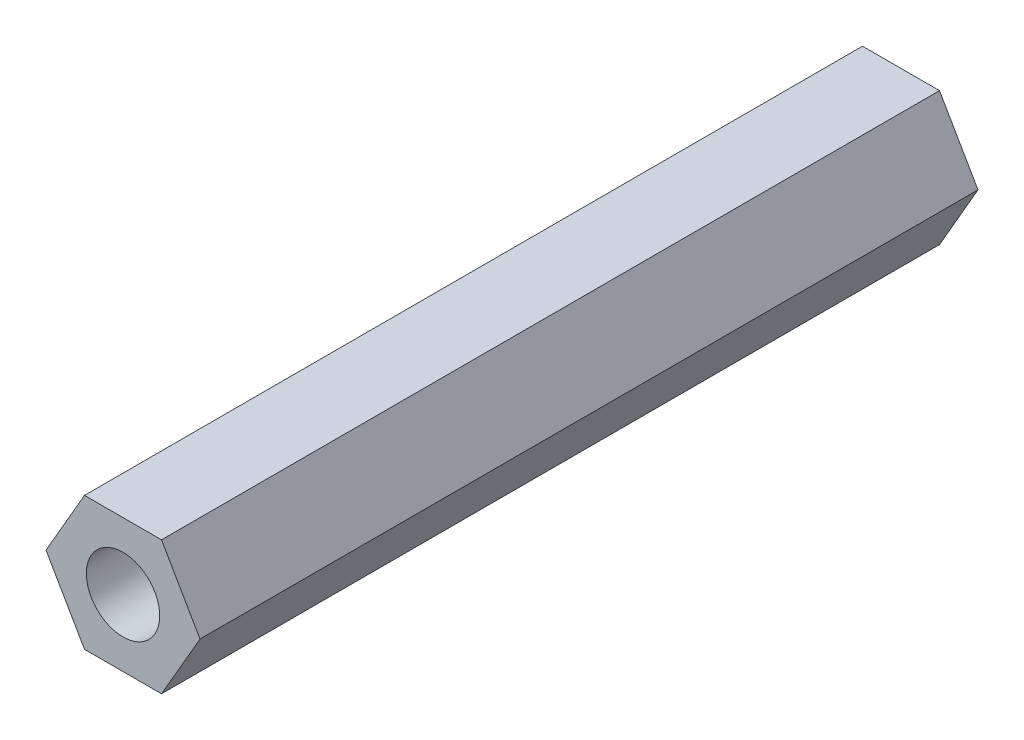
SolidWorks part; units mm, degrees
material "普通碳钢"
ref_plane "前视" through (0, 0, 0) normal (0, 0, 1) x (1, 0, 0)
ref_plane "上视" through (0, 0, 0) normal (0, 1, 0) x (1, 0, 0)
ref_plane "右视" through (0, 0, 0) normal (1, 0, 0) x (0, 0, -1)
sketch "草图1" plane through (0, 0, 0) normal (0, 0, 1) x (1, 0, 0)
  line L0 (0, 0) -> (3.4641, 0)
  line L1 (3.4641, 0) -> (5.1962, -3)
  line L2 (5.1962, -3) -> (3.4641, -6)
  line L3 (3.4641, -6) -> (0, -6)
  line L4 (0, -6) -> (-1.7321, -3)
  line L5 (-1.7321, -3) -> (0, 0)
  dimension "D1" = 6
  dimension "D2" = 6
extrude "凸台-拉伸1" add sketch "草图1" along normal blind 35
hole_wizard "M4 螺纹孔1" positions "草图3" profile "草图2" tap size "M4" standard "GB" end condition through all
sketch "草图3" plane through (0, 0, 35) normal (0, 0, 1) x (1, 0, 0)
  line L0 (-1.7321, -3) -> (5.1962, -3) construction
  line L2 (1.7321, 0) -> (1.7321, -6) construction
  line L3 (3.4641, 0) -> (0, 0) construction
  line L4 (0, -6) -> (3.4641, -6) construction
  point P0 (1.7321, -3)
cosmetic thread "孔螺蚊线1" parameters "D2"=4
sketch "草图2" plane through (1.7321, -3, 35) normal (1, 0, 0) x (0, -1, 0)
  line L0 (0, 0) -> (0, 35)
  line L1 (0, 35) -> (1.65, 35)
  line L2 (1.65, 35) -> (1.65, 0)
  line L5 (1.65, 0) -> (0, 0)
  line L11 (0, -6.35) -> (0, 107.95) construction
  dimension "通孔螺纹孔钻头直径" = 3.3
  dimension "通孔螺纹孔钻头深度" = 35
